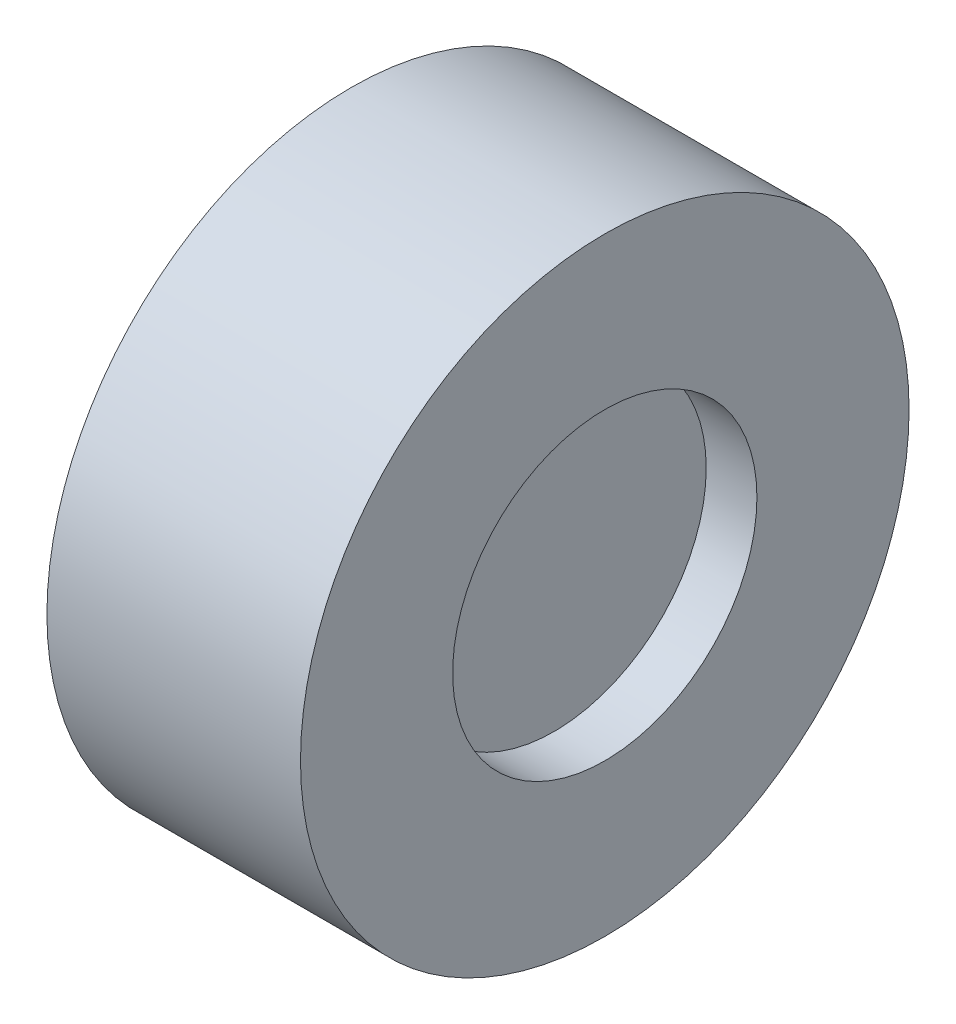
SolidWorks part; units mm, degrees
ref_plane "Front Plane" through (0, 0, 0) normal (0, 0, 1) x (1, 0, 0)
ref_plane "Top Plane" through (0, 0, 0) normal (0, 1, 0) x (1, 0, 0)
ref_plane "Right Plane" through (0, 0, 0) normal (1, 0, 0) x (0, 0, -1)
sketch "Sketch1" plane through (0, 0, 0) normal (1, 0, 0) x (0, 0, -1)
  circle A1 centre (0, 0) radius 12
extrude "Boss-Extrude1" add sketch "Sketch1" along normal blind 10
sketch "Sketch2" plane through (0, 0, 0) normal (-1, 0, 0) x (0, 0, 1)
  circle A0 centre (0, 0) radius 1.5
extrude "Cut-Extrude1" cut sketch "Sketch2" against normal blind 0.5 contours A0
sketch "Sketch3" plane through (10, 0, 0) normal (1, 0, 0) x (0, 0, -1)
  circle A0 centre (0, 0) radius 6
extrude "Cut-Extrude2" cut sketch "Sketch3" against normal blind 2
